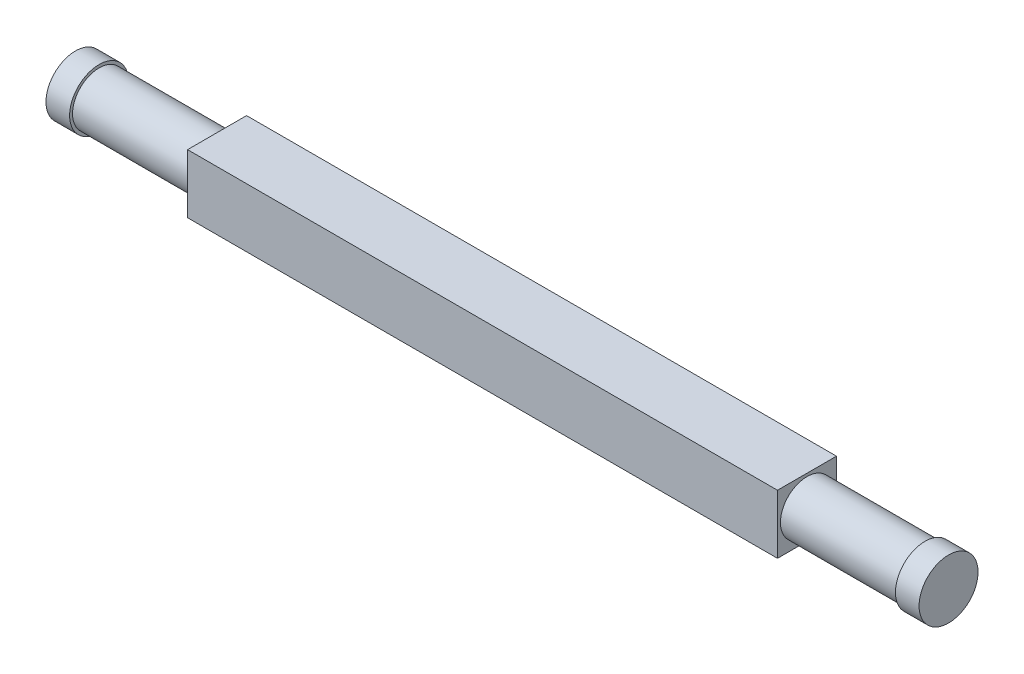
SolidWorks part; units mm, degrees
ref_plane "Plano frontal" through (0, 0, 0) normal (0, 0, 1) x (1, 0, 0)
ref_plane "Plano superior" through (0, 0, 0) normal (0, 1, 0) x (1, 0, 0)
ref_plane "Plano direito" through (0, 0, 0) normal (1, 0, 0) x (0, 0, -1)
sketch "Esboço1" plane through (0, 0, 0) normal (0, 0, 1) x (1, 0, 0)
  line L1 (0, 0) -> (-50, 0)
  line L2 (0, 0) -> (0, -5)
  line L3 (0, -5) -> (-50, -5)
  line L4 (-50, 0) -> (-50, -5)
  dimension "D1" = 5
  dimension "D2" = 50
extrude "Ressalto-extrusão1" add sketch "Esboço1" along normal blind 5
sketch "Esboço2" plane through (-50, 0, 0) normal (-1, 0, 0) x (0, 0, 1)
  line L0 (0, 0) -> (5, -5) construction
  line L1 (5, 0) -> (0, -5) construction
  circle A0 centre (2.5, -2.5) radius 2.25
  dimension "D1" = 4.5
extrude "Ressalto-extrusão2" add sketch "Esboço2" along normal blind 10
sketch "Esboço3" plane through (-60, 0, 0) normal (-1, 0, 0) x (0, 0, 1)
  circle A0 centre (2.5, -2.5) radius 2.5
  dimension "D1" = 5
extrude "Ressalto-extrusão3" add sketch "Esboço3" along normal blind 2
ref_plane "Plano1" through (-25, 0, 0) normal (-1, 0, 0) x (0, 0, 1)
mirror "Espelhar1" about plane through (-25, 0, 0) normal (-1, 0, 0) of "Ressalto-extrusão3", "Ressalto-extrusão2"
